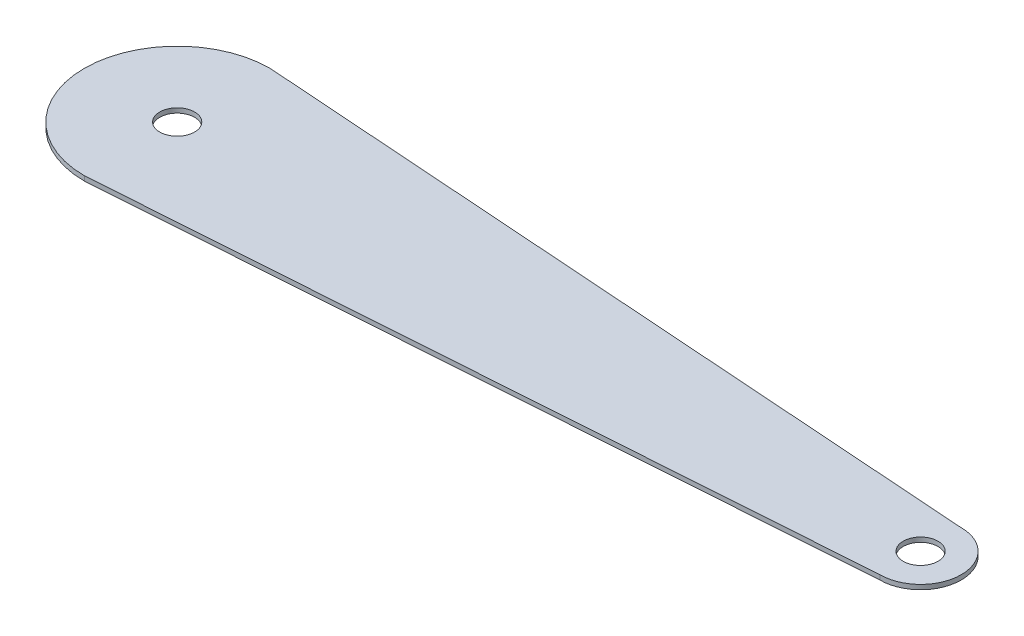
SolidWorks part; units mm, degrees
ref_plane "Front Plane" through (0, 0, 0) normal (0, 0, 1) x (1, 0, 0)
ref_plane "Top Plane" through (0, 0, 0) normal (0, 1, 0) x (1, 0, 0)
ref_plane "Right Plane" through (0, 0, 0) normal (1, 0, 0) x (0, 0, -1)
sketch "Sketch3" plane through (0, 0, 0) normal (0, 1, 0) x (1, 0, 0)
  line L0 (-203.2, 50.8) -> (203.2, 22.225)
  line L5 (203.2, -22.225) -> (-203.2, -50.8)
  line L6 (-203.2, 0) -> (203.2, 0) construction
  arc A0 (-203.2, 50.8) -> (-203.2, -50.8) centre (-203.2, 0) ccw
  arc A1 (203.2, -22.225) -> (203.2, 22.225) centre (203.2, 0) ccw
  point P7 (289.2641, 0)
  point P9 (0, 0)
  dimension "D1" = 101.6
  dimension "D2" = 44.45
  dimension "D3" = 406.4
extrude "Boss-Extrude1" add sketch "Sketch3" along normal blind 2.54
sketch "Sketch4" plane through (0, 2.54, 0) normal (0, 1, 0) x (1, 0, 0)
  circle A0 centre (-203.2, 0) radius 9.525
  circle A1 centre (203.2, 0) radius 9.525
  arc A2 (203.2, -22.225) -> (203.2, 22.225) centre (203.2, 0) ccw construction
  arc A3 (-203.2, 50.8) -> (-203.2, -50.8) centre (-203.2, 0) ccw construction
  dimension "D1" = 19.05
extrude "Cut-Extrude1" cut sketch "Sketch4" against normal blind 175.768
